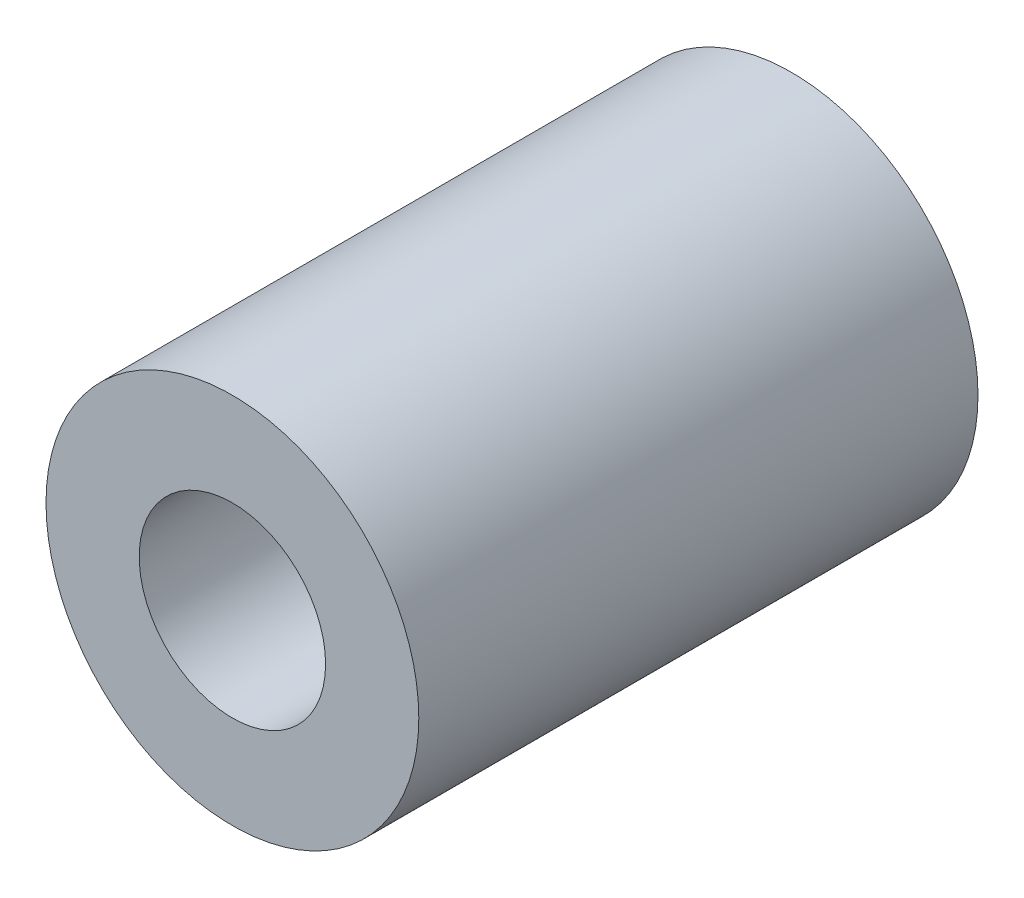
SolidWorks part; units mm, degrees
ref_plane "Front Plane" through (0, 0, 0) normal (0, 0, 1) x (1, 0, 0)
ref_plane "Top Plane" through (0, 0, 0) normal (0, 1, 0) x (1, 0, 0)
ref_plane "Right Plane" through (0, 0, 0) normal (1, 0, 0) x (0, 0, -1)
sketch "Sketch1" plane through (0, 0, 0) normal (0, 0, 1) x (1, 0, 0)
  circle A0 centre (0, 0) radius 5
  dimension "D1" = 10
extrude "Boss-Extrude1" add sketch "Sketch1" along normal blind 15
sketch "Sketch2" plane through (0, 0, 15) normal (0, 0, 1) x (1, 0, 0)
  circle A0 centre (0, 0) radius 2.5
  dimension "D1" = 5
extrude "Cut-Extrude1" cut sketch "Sketch2" against normal blind 4
chamfer "Chamfer1" [suppressed] distance 1 angle 45
